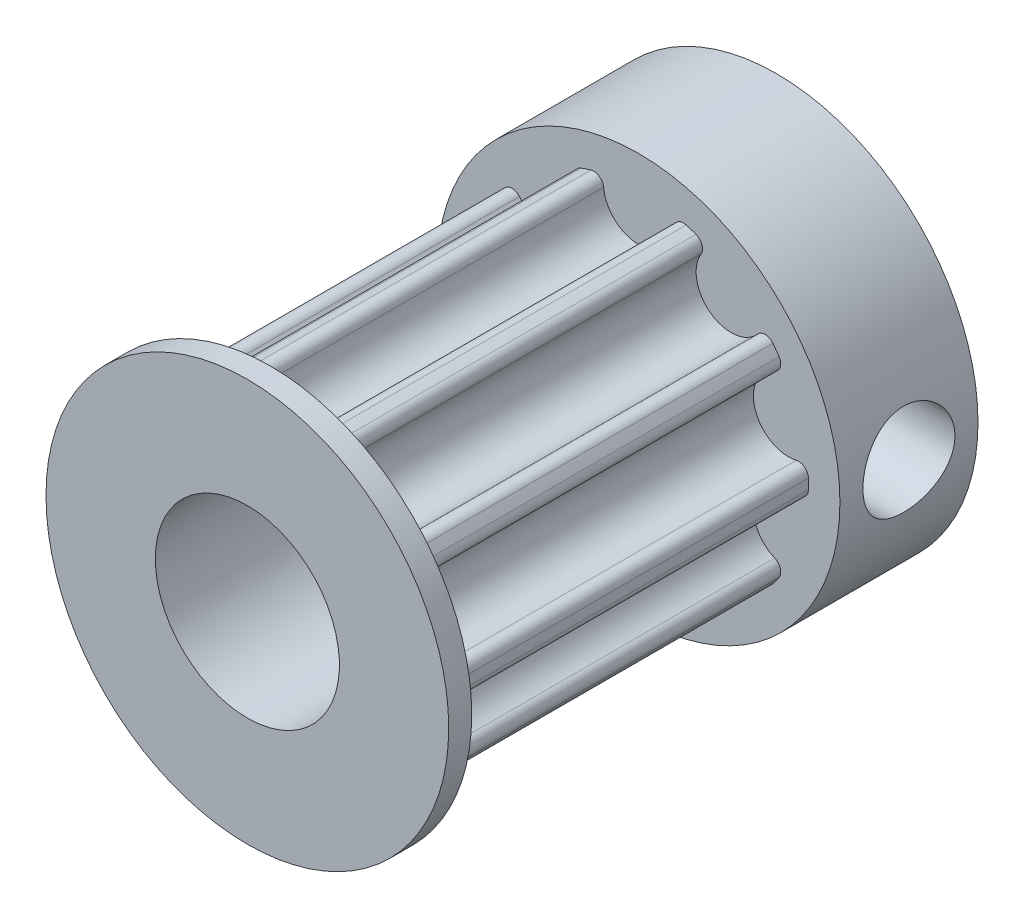
SolidWorks part; units mm, degrees
ref_plane "Front Plane" through (0, 0, 0) normal (0, 0, 1) x (1, 0, 0)
ref_plane "Top Plane" through (0, 0, 0) normal (0, 1, 0) x (1, 0, 0)
ref_plane "Right Plane" through (0, 0, 0) normal (1, 0, 0) x (0, 0, -1)
sketch "Sketch1" plane through (0, 0, 0) normal (0, 0, 1) x (1, 0, 0)
  line L0 (0, 0) -> (0, 13.1193) construction
  line L1 (0, 0) -> (18.7403, 0) construction
  line L2 (0, 0) -> (5.7681, 7.9392) construction
  arc A2 (0, 5.325) -> (1.519, 6.7149) centre (0, 6.85) ccw
  arc A3 (2.0677, 7.0896) -> (1.519, 6.7149) centre (1.9473, 6.6768) ccw
  arc A4 (2.718, 6.3253) -> (3.13, 4.308) centre (4.0263, 5.5418) ccw
  arc A5 (2.718, 6.3253) -> (2.4944, 6.951) centre (2.3491, 6.5463) ccw
  arc A6 (2.4944, 6.951) -> (2.0677, 7.0896) centre (0, 0) ccw
  arc A7 (3.13, 4.308) -> (5.1758, 4.5396) centre (4.0263, 5.5418) ccw
  arc A8 (5.84, 4.5203) -> (5.1758, 4.5396) centre (5.5, 4.2571) ccw
  arc A9 (6.1037, 4.1573) -> (5.84, 4.5203) centre (0, 0) ccw
  arc A10 (5.9169, 3.5197) -> (6.1037, 4.1573) centre (5.7483, 3.9153) ccw
  arc A11 (5.9169, 3.5197) -> (5.0644, 1.6455) centre (6.5147, 2.1168) ccw
  arc A12 (5.0644, 1.6455) -> (6.8557, 0.6304) centre (6.5147, 2.1168) ccw
  arc A13 (7.3816, 0.2243) -> (6.8557, 0.6304) centre (6.9518, 0.2112) ccw
  arc A14 (7.3816, -0.2243) -> (7.3816, 0.2243) centre (0, 0) ccw
  arc A15 (6.8557, -0.6304) -> (7.3816, -0.2243) centre (6.9518, -0.2112) ccw
  arc A16 (6.8557, -0.6304) -> (5.0644, -1.6455) centre (6.5147, -2.1168) ccw
  arc A17 (5.0644, -1.6455) -> (5.9169, -3.5197) centre (6.5147, -2.1168) ccw
  arc A18 (6.1037, -4.1573) -> (5.9169, -3.5197) centre (5.7483, -3.9153) ccw
  arc A19 (5.84, -4.5203) -> (6.1037, -4.1573) centre (0, 0) ccw
  arc A20 (5.1758, -4.5396) -> (5.84, -4.5203) centre (5.5, -4.2571) ccw
  arc A21 (5.1758, -4.5396) -> (3.13, -4.308) centre (4.0263, -5.5418) ccw
  arc A22 (3.13, -4.308) -> (2.718, -6.3253) centre (4.0263, -5.5418) ccw
  arc A23 (2.4944, -6.951) -> (2.718, -6.3253) centre (2.3491, -6.5463) ccw
  arc A24 (2.0677, -7.0896) -> (2.4944, -6.951) centre (0, 0) ccw
  arc A25 (1.519, -6.7149) -> (2.0677, -7.0896) centre (1.9473, -6.6768) ccw
  arc A26 (1.519, -6.7149) -> (0, -5.325) centre (0, -6.85) ccw
  arc A27 (0, -5.325) -> (-1.519, -6.7149) centre (0, -6.85) ccw
  arc A28 (-2.0677, -7.0896) -> (-1.519, -6.7149) centre (-1.9473, -6.6768) ccw
  arc A29 (-2.4944, -6.951) -> (-2.0677, -7.0896) centre (0, 0) ccw
  arc A30 (-2.718, -6.3253) -> (-2.4944, -6.951) centre (-2.3491, -6.5463) ccw
  arc A31 (-2.718, -6.3253) -> (-3.13, -4.308) centre (-4.0263, -5.5418) ccw
  arc A32 (-3.13, -4.308) -> (-5.1758, -4.5396) centre (-4.0263, -5.5418) ccw
  arc A33 (-5.84, -4.5203) -> (-5.1758, -4.5396) centre (-5.5, -4.2571) ccw
  arc A34 (-6.1037, -4.1573) -> (-5.84, -4.5203) centre (0, 0) ccw
  arc A35 (-5.9169, -3.5197) -> (-6.1037, -4.1573) centre (-5.7483, -3.9153) ccw
  arc A36 (-5.9169, -3.5197) -> (-5.0644, -1.6455) centre (-6.5147, -2.1168) ccw
  arc A37 (-5.0644, -1.6455) -> (-6.8557, -0.6304) centre (-6.5147, -2.1168) ccw
  arc A38 (-7.3816, -0.2243) -> (-6.8557, -0.6304) centre (-6.9518, -0.2112) ccw
  arc A39 (-7.3816, 0.2243) -> (-7.3816, -0.2243) centre (0, 0) ccw
  arc A40 (-6.8557, 0.6304) -> (-7.3816, 0.2243) centre (-6.9518, 0.2112) ccw
  arc A41 (-6.8557, 0.6304) -> (-5.0644, 1.6455) centre (-6.5147, 2.1168) ccw
  arc A42 (-5.0644, 1.6455) -> (-5.9169, 3.5197) centre (-6.5147, 2.1168) ccw
  arc A43 (-6.1037, 4.1573) -> (-5.9169, 3.5197) centre (-5.7483, 3.9153) ccw
  arc A44 (-5.84, 4.5203) -> (-6.1037, 4.1573) centre (0, 0) ccw
  arc A45 (-5.1758, 4.5396) -> (-5.84, 4.5203) centre (-5.5, 4.2571) ccw
  arc A46 (-5.1758, 4.5396) -> (-3.13, 4.308) centre (-4.0263, 5.5418) ccw
  arc A47 (-3.13, 4.308) -> (-2.718, 6.3253) centre (-4.0263, 5.5418) ccw
  arc A48 (-2.4944, 6.951) -> (-2.718, 6.3253) centre (-2.3491, 6.5463) ccw
  arc A49 (-2.0677, 7.0896) -> (-2.4944, 6.951) centre (0, 0) ccw
  arc A50 (-1.519, 6.7149) -> (-2.0677, 7.0896) centre (-1.9473, 6.6768) ccw
  arc A51 (-1.519, 6.7149) -> (0, 5.325) centre (0, 6.85) ccw
  point P109 (0, 0)
  dimension "D1" = 10
  dimension "D3" = 3.05
  dimension "D4" = 0.86
  dimension "D6" = 3.05
  dimension "D7" = 0.86
extrude "Boss-Extrude1" add sketch "Sketch1" along normal blind 16
sketch "Sketch2" plane through (0, 0, 16) normal (0, 0, 1) x (1, 0, 0)
  circle A0 centre (0, 0) radius 8.75
  dimension "D1" = 17.5
extrude "Boss-Extrude2" add sketch "Sketch2" along normal blind 1
sketch "Sketch3" plane through (0, 0, 0) normal (0, 0, -1) x (-1, 0, 0)
  circle A0 centre (0, 0) radius 8.75
  dimension "D1" = 17.5
extrude "Boss-Extrude3" add sketch "Sketch3" along normal blind 6
sketch "Sketch4" plane through (0, 0, -6) normal (0, 0, -1) x (-1, 0, 0)
  circle A0 centre (0, 0) radius 4
  dimension "D1" = 8
extrude "Cut-Extrude1" cut sketch "Sketch4" against normal through all
sketch "Sketch5" plane through (0, 0, 0) normal (0, 1, 0) x (1, 0, 0)
  line L0 (4, 6) -> (-4, 6) construction
  circle A0 centre (0, 3) radius 2
  dimension "D1" = 4
  dimension "D2" = 3
extrude "Cut-Extrude2" cut sketch "Sketch5" against normal through all
pattern_circular "CirPattern1" count 2 every 90 about axis through (0, 0, 16) along (0, 0, -1) of "Cut-Extrude2"
sketch "Sketch6" plane through (0, 0, 17) normal (0, 0, 1) x (1, 0, 0)
  line L0 (0, 0) -> (15.4835, 0)
